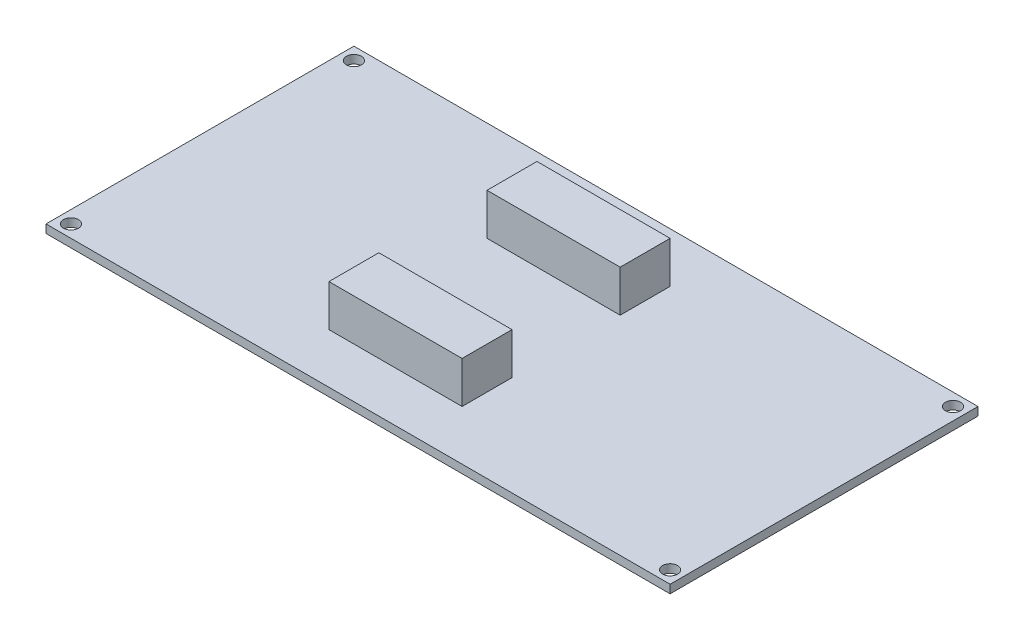
SolidWorks part; units mm, degrees
ref_plane "Front Plane" through (0, 0, 0) normal (0, 0, 1) x (1, 0, 0)
ref_plane "Top Plane" through (0, 0, 0) normal (0, 1, 0) x (1, 0, 0)
ref_plane "Right Plane" through (0, 0, 0) normal (1, 0, 0) x (0, 0, -1)
sketch "Sketch1" plane through (0, 0, 0) normal (0, 1, 0) x (1, 0, 0)
  line L1 (59.5312, 29.3688) -> (-59.5312, 29.3687)
  line L2 (59.5312, 29.3688) -> (59.5313, -29.3687)
  line L3 (59.5313, -29.3687) -> (-59.5312, -29.3687)
  line L4 (-59.5312, 29.3687) -> (-59.5312, -29.3687)
  line L5 (59.5312, 29.3688) -> (-59.5312, -29.3687) construction
  line L6 (59.5313, -29.3687) -> (-59.5312, 29.3687) construction
  point P0 (0, 0)
  dimension "D1" = 119.0625
  dimension "D2" = 58.7375
extrude "Boss-Extrude1" add sketch "Sketch1" along normal blind 1.5875
sketch "Sketch2" plane through (0, 1.5875, 0) normal (0, 1, 0) x (1, 0, 0)
  line L1 (-15.0812, -19.8437) -> (10.3188, -19.8437)
  line L2 (-15.0812, -19.8437) -> (-15.0812, -10.3187)
  line L3 (-15.0812, -10.3187) -> (10.3188, -10.3187)
  line L4 (10.3188, -19.8437) -> (10.3188, -10.3187)
  line L5 (-15.0812, -19.8437) -> (10.3188, -10.3187) construction
  line L6 (-15.0812, -10.3187) -> (10.3188, -19.8437) construction
  point P0 (-2.3812, -15.0812)
  dimension "D1" = 49.2125
  dimension "D2" = 9.525
  dimension "D3" = 9.525
  dimension "D4" = 25.4
extrude "Boss-Extrude2" add sketch "Sketch2" along normal blind 7.9375
mirror "Mirror1" about plane through (0, 0, 0) normal (0, 0, 1) of "Boss-Extrude2"
sketch "Sketch3" plane through (0, 1.5875, 0) normal (0, 1, 0) x (1, 0, 0)
  circle A0 centre (-57.15, -26.9875) radius 1.4288
  dimension "D1" = 2.3813
  dimension "D2" = 2.8575
  dimension "D3" = 2.3813
extrude "Cut-Extrude1" cut sketch "Sketch3" against normal through all
mirror "Mirror2" about plane through (0, 0, 0) normal (1, 0, 0) of "Cut-Extrude1" second plane through (0, 0, 0) second plane normal (0, 0, 1)
